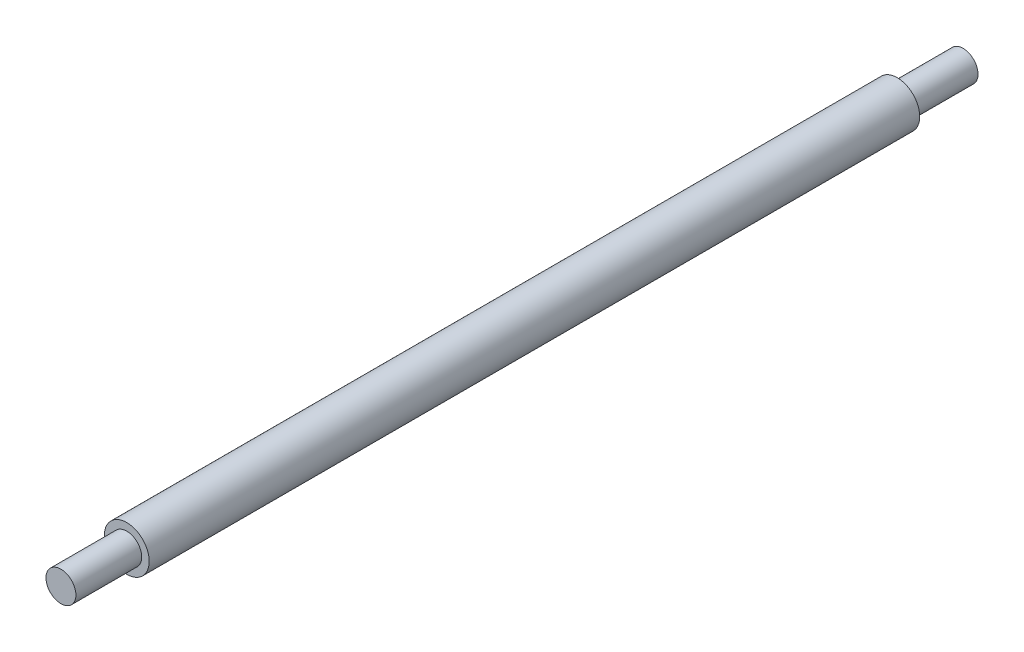
SolidWorks part; units mm, degrees
material "6061 Alloy"
ref_plane "Front" through (0, 0, 0) normal (0, 0, 1) x (1, 0, 0)
ref_plane "Top" through (0, 0, 0) normal (0, 1, 0) x (1, 0, 0)
ref_plane "Right" through (0, 0, 0) normal (1, 0, 0) x (0, 0, -1)
sketch "Sketch1" plane through (0, 0, 0) normal (0, 0, 1) x (1, 0, 0)
  circle A0 centre (0, 0) radius 9.525
  dimension "D1" = 19.05
extrude "Boss-Extrude1" add sketch "Sketch1" along normal blind 327.025
sketch "Sketch2" plane through (0, 0, 327.025) normal (0, 0, 1) x (1, 0, 0)
  circle A0 centre (0, 0) radius 6.35
  dimension "D1" = 12.7
extrude "Boss-Extrude2" add sketch "Sketch2" along normal blind 27.94
sketch "Sketch3" plane through (0, 0, 0) normal (0, 0, -1) x (-1, 0, 0)
  circle A0 centre (0, 0) radius 6.35
  dimension "D1" = 12.7
extrude "Boss-Extrude3" add sketch "Sketch3" along normal blind 27.94
